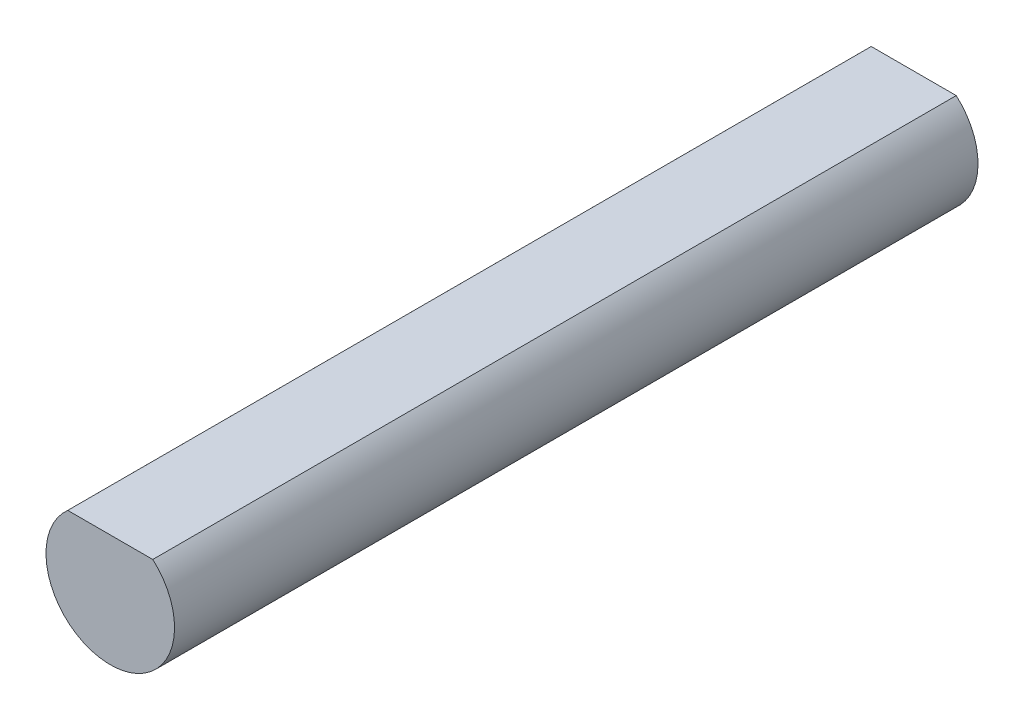
SolidWorks part; units mm, degrees
ref_plane "Front Plane" through (0, 0, 0) normal (0, 0, 1) x (1, 0, 0)
ref_plane "Top Plane" through (0, 0, 0) normal (0, 1, 0) x (1, 0, 0)
ref_plane "Right Plane" through (0, 0, 0) normal (1, 0, 0) x (0, 0, -1)
sketch "Sketch2" plane through (0, 0, 0) normal (0, 0, 1) x (1, 0, 0)
  line L0 (-1.3229, 1.5) -> (1.3229, 1.5)
  arc A0 (-1.3229, 1.5) -> (1.3229, 1.5) centre (0, 0) ccw
  dimension "D1" = 4
  dimension "D2" = 1.5
extrude "Boss-Extrude1" add sketch "Sketch2" along normal blind 25
